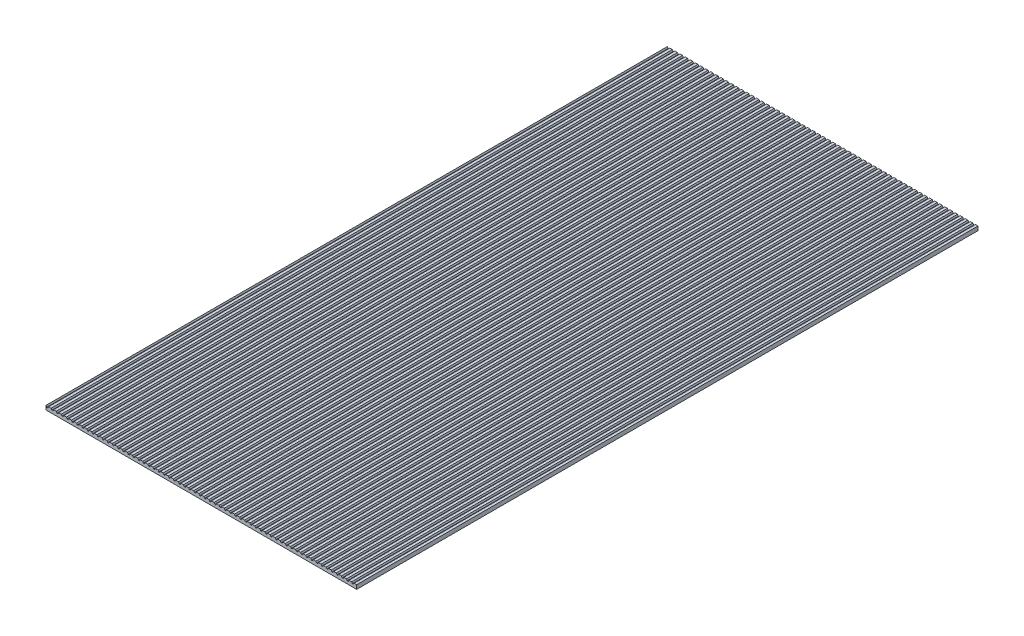
SolidWorks part; units mm, degrees
ref_plane "Front Plane" through (0, 0, 0) normal (0, 0, 1) x (1, 0, 0)
ref_plane "Top Plane" through (0, 0, 0) normal (0, 1, 0) x (1, 0, 0)
ref_plane "Right Plane" through (0, 0, 0) normal (1, 0, 0) x (0, 0, -1)
sketch "Sketch1" plane through (0, 0, 0) normal (0, 1, 0) x (1, 0, 0)
  line L1 (0, 0) -> (1220, 0)
  line L2 (0, 0) -> (0, 2440)
  line L3 (0, 2440) -> (1220, 2440)
  line L4 (1220, 0) -> (1220, 2440)
  dimension "D1" = 1220
  dimension "D2" = 2440
extrude "Boss-Extrude1" add sketch "Sketch1" along normal blind 16
sketch "Sketch2" plane through (0, 0, 0) normal (0, 0, 1) x (1, 0, 0)
  line L0 (0, 16) -> (1220, 16) construction
  line L1 (0, 16) -> (3, 10.8038)
  line L2 (3, 10.8038) -> (7, 10.8038)
  line L3 (7, 10.8038) -> (10, 16)
  line L4 (10, 16) -> (0, 16)
  line L5 (1220, 16) -> (1220, 0) construction
  line L6 (0, 0) -> (1220, 0) construction
  line L7 (30, 16) -> (20, 16)
  line L8 (20, 16) -> (23, 10.8038)
  line L9 (23, 10.8038) -> (27, 10.8038)
  line L10 (27, 10.8038) -> (30, 16)
  line L11 (50, 16) -> (40, 16)
  line L12 (40, 16) -> (43, 10.8038)
  line L13 (43, 10.8038) -> (47, 10.8038)
  line L14 (47, 10.8038) -> (50, 16)
  line L15 (70, 16) -> (60, 16)
  line L16 (60, 16) -> (63, 10.8038)
  line L17 (63, 10.8038) -> (67, 10.8038)
  line L18 (67, 10.8038) -> (70, 16)
  line L19 (90, 16) -> (80, 16)
  line L20 (80, 16) -> (83, 10.8038)
  line L21 (83, 10.8038) -> (87, 10.8038)
  line L22 (87, 10.8038) -> (90, 16)
  line L23 (110, 16) -> (100, 16)
  line L24 (100, 16) -> (103, 10.8038)
  line L25 (103, 10.8038) -> (107, 10.8038)
  line L26 (107, 10.8038) -> (110, 16)
  line L27 (130, 16) -> (120, 16)
  line L28 (120, 16) -> (123, 10.8038)
  line L29 (123, 10.8038) -> (127, 10.8038)
  line L30 (127, 10.8038) -> (130, 16)
  line L31 (150, 16) -> (140, 16)
  line L32 (140, 16) -> (143, 10.8038)
  line L33 (143, 10.8038) -> (147, 10.8038)
  line L34 (147, 10.8038) -> (150, 16)
  line L35 (170, 16) -> (160, 16)
  line L36 (160, 16) -> (163, 10.8038)
  line L37 (163, 10.8038) -> (167, 10.8038)
  line L38 (167, 10.8038) -> (170, 16)
  line L39 (190, 16) -> (180, 16)
  line L40 (180, 16) -> (183, 10.8038)
  line L41 (183, 10.8038) -> (187, 10.8038)
  line L42 (187, 10.8038) -> (190, 16)
  line L43 (210, 16) -> (200, 16)
  line L44 (200, 16) -> (203, 10.8038)
  line L45 (203, 10.8038) -> (207, 10.8038)
  line L46 (207, 10.8038) -> (210, 16)
  line L47 (230, 16) -> (220, 16)
  line L48 (220, 16) -> (223, 10.8038)
  line L49 (223, 10.8038) -> (227, 10.8038)
  line L50 (227, 10.8038) -> (230, 16)
  line L51 (250, 16) -> (240, 16)
  line L52 (240, 16) -> (243, 10.8038)
  line L53 (243, 10.8038) -> (247, 10.8038)
  line L54 (247, 10.8038) -> (250, 16)
  line L55 (270, 16) -> (260, 16)
  line L56 (260, 16) -> (263, 10.8038)
  line L57 (263, 10.8038) -> (267, 10.8038)
  line L58 (267, 10.8038) -> (270, 16)
  line L59 (290, 16) -> (280, 16)
  line L60 (280, 16) -> (283, 10.8038)
  line L61 (283, 10.8038) -> (287, 10.8038)
  line L62 (287, 10.8038) -> (290, 16)
  line L63 (310, 16) -> (300, 16)
  line L64 (300, 16) -> (303, 10.8038)
  line L65 (303, 10.8038) -> (307, 10.8038)
  line L66 (307, 10.8038) -> (310, 16)
  line L67 (330, 16) -> (320, 16)
  line L68 (320, 16) -> (323, 10.8038)
  line L69 (323, 10.8038) -> (327, 10.8038)
  line L70 (327, 10.8038) -> (330, 16)
  line L71 (350, 16) -> (340, 16)
  line L72 (340, 16) -> (343, 10.8038)
  line L73 (343, 10.8038) -> (347, 10.8038)
  line L74 (347, 10.8038) -> (350, 16)
  line L75 (370, 16) -> (360, 16)
  line L76 (360, 16) -> (363, 10.8038)
  line L77 (363, 10.8038) -> (367, 10.8038)
  line L78 (367, 10.8038) -> (370, 16)
  line L79 (390, 16) -> (380, 16)
  line L80 (380, 16) -> (383, 10.8038)
  line L81 (383, 10.8038) -> (387, 10.8038)
  line L82 (387, 10.8038) -> (390, 16)
  line L83 (410, 16) -> (400, 16)
  line L84 (400, 16) -> (403, 10.8038)
  line L85 (403, 10.8038) -> (407, 10.8038)
  line L86 (407, 10.8038) -> (410, 16)
  line L87 (430, 16) -> (420, 16)
  line L88 (420, 16) -> (423, 10.8038)
  line L89 (423, 10.8038) -> (427, 10.8038)
  line L90 (427, 10.8038) -> (430, 16)
  line L91 (450, 16) -> (440, 16)
  line L92 (440, 16) -> (443, 10.8038)
  line L93 (443, 10.8038) -> (447, 10.8038)
  line L94 (447, 10.8038) -> (450, 16)
  line L95 (470, 16) -> (460, 16)
  line L96 (460, 16) -> (463, 10.8038)
  line L97 (463, 10.8038) -> (467, 10.8038)
  line L98 (467, 10.8038) -> (470, 16)
  line L99 (490, 16) -> (480, 16)
  line L100 (480, 16) -> (483, 10.8038)
  line L101 (483, 10.8038) -> (487, 10.8038)
  line L102 (487, 10.8038) -> (490, 16)
  line L103 (510, 16) -> (500, 16)
  line L104 (500, 16) -> (503, 10.8038)
  line L105 (503, 10.8038) -> (507, 10.8038)
  line L106 (507, 10.8038) -> (510, 16)
  line L107 (530, 16) -> (520, 16)
  line L108 (520, 16) -> (523, 10.8038)
  line L109 (523, 10.8038) -> (527, 10.8038)
  line L110 (527, 10.8038) -> (530, 16)
  line L111 (550, 16) -> (540, 16)
  line L112 (540, 16) -> (543, 10.8038)
  line L113 (543, 10.8038) -> (547, 10.8038)
  line L114 (547, 10.8038) -> (550, 16)
  line L115 (570, 16) -> (560, 16)
  line L116 (560, 16) -> (563, 10.8038)
  line L117 (563, 10.8038) -> (567, 10.8038)
  line L118 (567, 10.8038) -> (570, 16)
  line L119 (590, 16) -> (580, 16)
  line L120 (580, 16) -> (583, 10.8038)
  line L121 (583, 10.8038) -> (587, 10.8038)
  line L122 (587, 10.8038) -> (590, 16)
  line L123 (610, 16) -> (600, 16)
  line L124 (600, 16) -> (603, 10.8038)
  line L125 (603, 10.8038) -> (607, 10.8038)
  line L126 (607, 10.8038) -> (610, 16)
  line L127 (630, 16) -> (620, 16)
  line L128 (620, 16) -> (623, 10.8038)
  line L129 (623, 10.8038) -> (627, 10.8038)
  line L130 (627, 10.8038) -> (630, 16)
  line L131 (650, 16) -> (640, 16)
  line L132 (640, 16) -> (643, 10.8038)
  line L133 (643, 10.8038) -> (647, 10.8038)
  line L134 (647, 10.8038) -> (650, 16)
  line L135 (670, 16) -> (660, 16)
  line L136 (660, 16) -> (663, 10.8038)
  line L137 (663, 10.8038) -> (667, 10.8038)
  line L138 (667, 10.8038) -> (670, 16)
  line L139 (690, 16) -> (680, 16)
  line L140 (680, 16) -> (683, 10.8038)
  line L141 (683, 10.8038) -> (687, 10.8038)
  line L142 (687, 10.8038) -> (690, 16)
  line L143 (710, 16) -> (700, 16)
  line L144 (700, 16) -> (703, 10.8038)
  line L145 (703, 10.8038) -> (707, 10.8038)
  line L146 (707, 10.8038) -> (710, 16)
  line L147 (730, 16) -> (720, 16)
  line L148 (720, 16) -> (723, 10.8038)
  line L149 (723, 10.8038) -> (727, 10.8038)
  line L150 (727, 10.8038) -> (730, 16)
  line L151 (750, 16) -> (740, 16)
  line L152 (740, 16) -> (743, 10.8038)
  line L153 (743, 10.8038) -> (747, 10.8038)
  line L154 (747, 10.8038) -> (750, 16)
  line L155 (770, 16) -> (760, 16)
  line L156 (760, 16) -> (763, 10.8038)
  line L157 (763, 10.8038) -> (767, 10.8038)
  line L158 (767, 10.8038) -> (770, 16)
  line L159 (790, 16) -> (780, 16)
  line L160 (780, 16) -> (783, 10.8038)
  line L161 (783, 10.8038) -> (787, 10.8038)
  line L162 (787, 10.8038) -> (790, 16)
  line L163 (810, 16) -> (800, 16)
  line L164 (800, 16) -> (803, 10.8038)
  line L165 (803, 10.8038) -> (807, 10.8038)
  line L166 (807, 10.8038) -> (810, 16)
  line L167 (830, 16) -> (820, 16)
  line L168 (820, 16) -> (823, 10.8038)
  line L169 (823, 10.8038) -> (827, 10.8038)
  line L170 (827, 10.8038) -> (830, 16)
  line L171 (850, 16) -> (840, 16)
  line L172 (840, 16) -> (843, 10.8038)
  line L173 (843, 10.8038) -> (847, 10.8038)
  line L174 (847, 10.8038) -> (850, 16)
  line L175 (870, 16) -> (860, 16)
  line L176 (860, 16) -> (863, 10.8038)
  line L177 (863, 10.8038) -> (867, 10.8038)
  line L178 (867, 10.8038) -> (870, 16)
  line L179 (890, 16) -> (880, 16)
  line L180 (880, 16) -> (883, 10.8038)
  line L181 (883, 10.8038) -> (887, 10.8038)
  line L182 (887, 10.8038) -> (890, 16)
  line L183 (910, 16) -> (900, 16)
  line L184 (900, 16) -> (903, 10.8038)
  line L185 (903, 10.8038) -> (907, 10.8038)
  line L186 (907, 10.8038) -> (910, 16)
  line L187 (930, 16) -> (920, 16)
  line L188 (920, 16) -> (923, 10.8038)
  line L189 (923, 10.8038) -> (927, 10.8038)
  line L190 (927, 10.8038) -> (930, 16)
  line L191 (950, 16) -> (940, 16)
  line L192 (940, 16) -> (943, 10.8038)
  line L193 (943, 10.8038) -> (947, 10.8038)
  line L194 (947, 10.8038) -> (950, 16)
  line L195 (970, 16) -> (960, 16)
  line L196 (960, 16) -> (963, 10.8038)
  line L197 (963, 10.8038) -> (967, 10.8038)
  line L198 (967, 10.8038) -> (970, 16)
  line L199 (990, 16) -> (980, 16)
  line L200 (980, 16) -> (983, 10.8038)
  line L201 (983, 10.8038) -> (987, 10.8038)
  line L202 (987, 10.8038) -> (990, 16)
  line L203 (1010, 16) -> (1000, 16)
  line L204 (1000, 16) -> (1003, 10.8038)
  line L205 (1003, 10.8038) -> (1007, 10.8038)
  line L206 (1007, 10.8038) -> (1010, 16)
  line L207 (1030, 16) -> (1020, 16)
  line L208 (1020, 16) -> (1023, 10.8038)
  line L209 (1023, 10.8038) -> (1027, 10.8038)
  line L210 (1027, 10.8038) -> (1030, 16)
  line L211 (1050, 16) -> (1040, 16)
  line L212 (1040, 16) -> (1043, 10.8038)
  line L213 (1043, 10.8038) -> (1047, 10.8038)
  line L214 (1047, 10.8038) -> (1050, 16)
  line L215 (1070, 16) -> (1060, 16)
  line L216 (1060, 16) -> (1063, 10.8038)
  line L217 (1063, 10.8038) -> (1067, 10.8038)
  line L218 (1067, 10.8038) -> (1070, 16)
  line L219 (1090, 16) -> (1080, 16)
  line L220 (1080, 16) -> (1083, 10.8038)
  line L221 (1083, 10.8038) -> (1087, 10.8038)
  line L222 (1087, 10.8038) -> (1090, 16)
  line L223 (1110, 16) -> (1100, 16)
  line L224 (1100, 16) -> (1103, 10.8038)
  line L225 (1103, 10.8038) -> (1107, 10.8038)
  line L226 (1107, 10.8038) -> (1110, 16)
  line L227 (1130, 16) -> (1120, 16)
  line L228 (1120, 16) -> (1123, 10.8038)
  line L229 (1123, 10.8038) -> (1127, 10.8038)
  line L230 (1127, 10.8038) -> (1130, 16)
  line L231 (1150, 16) -> (1140, 16)
  line L232 (1140, 16) -> (1143, 10.8038)
  line L233 (1143, 10.8038) -> (1147, 10.8038)
  line L234 (1147, 10.8038) -> (1150, 16)
  line L235 (1170, 16) -> (1160, 16)
  line L236 (1160, 16) -> (1163, 10.8038)
  line L237 (1163, 10.8038) -> (1167, 10.8038)
  line L238 (1167, 10.8038) -> (1170, 16)
  line L239 (1190, 16) -> (1180, 16)
  line L240 (1180, 16) -> (1183, 10.8038)
  line L241 (1183, 10.8038) -> (1187, 10.8038)
  line L242 (1187, 10.8038) -> (1190, 16)
  line L243 (1210, 16) -> (1200, 16)
  line L244 (1200, 16) -> (1203, 10.8038)
  line L245 (1203, 10.8038) -> (1207, 10.8038)
  line L246 (1207, 10.8038) -> (1210, 16)
  dimension "D1" = 60
  dimension "D2" = 10
  dimension "D3" = 4
  dimension "D4" = 61
extrude "Cut-Extrude1" cut sketch "Sketch2" against normal blind 2440
